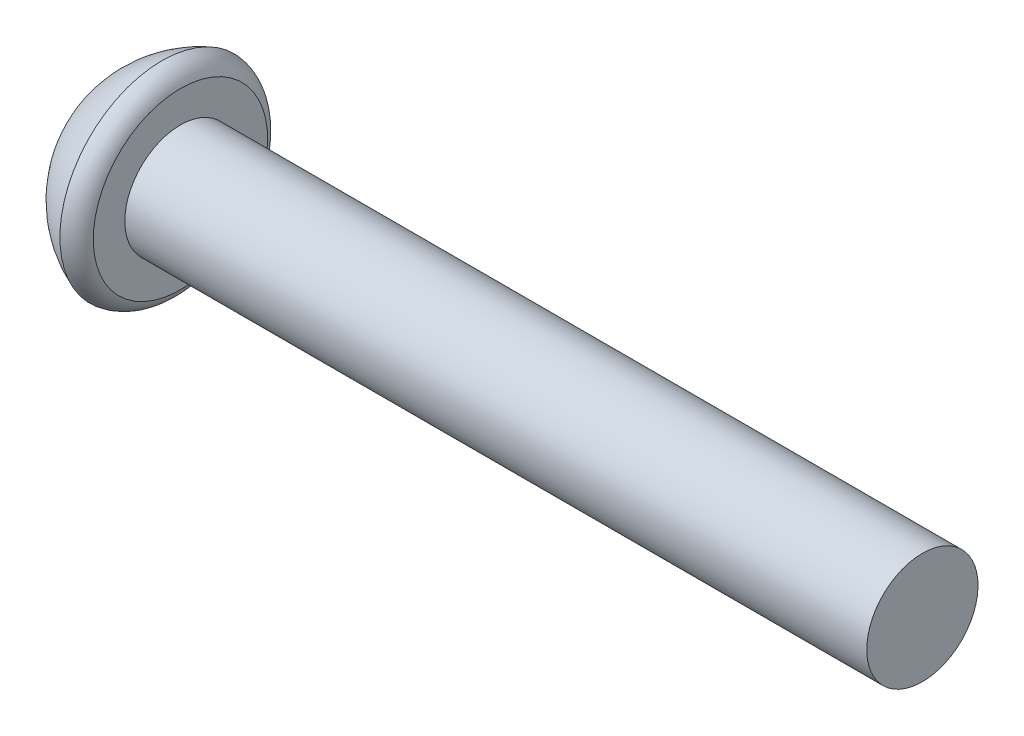
SolidWorks part; units mm, degrees
material "AISI 1020"
ref_plane "Front Plane" through (0, 0, 0) normal (0, 0, 1) x (1, 0, 0)
ref_plane "Top Plane" through (0, 0, 0) normal (0, 1, 0) x (1, 0, 0)
ref_plane "Right Plane" through (0, 0, 0) normal (1, 0, 0) x (0, 0, -1)
sketch "Sketch1" plane through (0, 0, 0) normal (0, 0, 1) x (1, 0, 0)
  line L0 (0, 0) -> (20, 0)
  line L1 (20, 0) -> (20, -1.5)
  line L2 (20, -1.5) -> (-2, -1.5)
  line L5 (0, 0.85) -> (0, 0)
  line L6 (-2, -1.5) -> (-2, 0)
  line L7 (-0.5, -1.5) -> (-0.5, 1.25) construction
  arc A1 (-2, 0) -> (-0.5, 1.25) centre (0.5389, -1.5217) cw
  arc A2 (-0.5, 1.25) -> (0, 0.85) centre (-0.567, 0.6538) cw
  dimension "D4" = 0.4
  dimension "D8" = 2.96
  dimension "D9" = 0.6
  dimension "D1" = 1.5
  dimension "D2" = 2
  dimension "D3" = 2.75
  dimension "D5" = 20
  dimension "D6" = 0.5
  dimension "D7" = 1.5
revolve "Revolve1" add sketch "Sketch1" angle 360 about L2
cosmetic thread "Cosmetic Thread1" parameters "D2"=2
sketch "Sketch2" plane through (-2, 0, 0) normal (-1, 0, 0) x (0, 0, 1)
  line L1 (0, -0.2298) -> (-1.1, -0.8649)
  line L2 (-1.1, -0.8649) -> (-1.1, -2.1351)
  line L3 (-1.1, -2.1351) -> (0, -2.7702)
  line L4 (0, -2.7702) -> (1.1, -2.1351)
  line L5 (1.1, -2.1351) -> (1.1, -0.8649)
  line L6 (1.1, -0.8649) -> (0, -0.2298)
  circle A0 centre (0, -1.5) radius 1.1 construction
  dimension "D1" = 2.2
extrude "Cut-Extrude1" cut sketch "Sketch2" against normal blind 1.5
